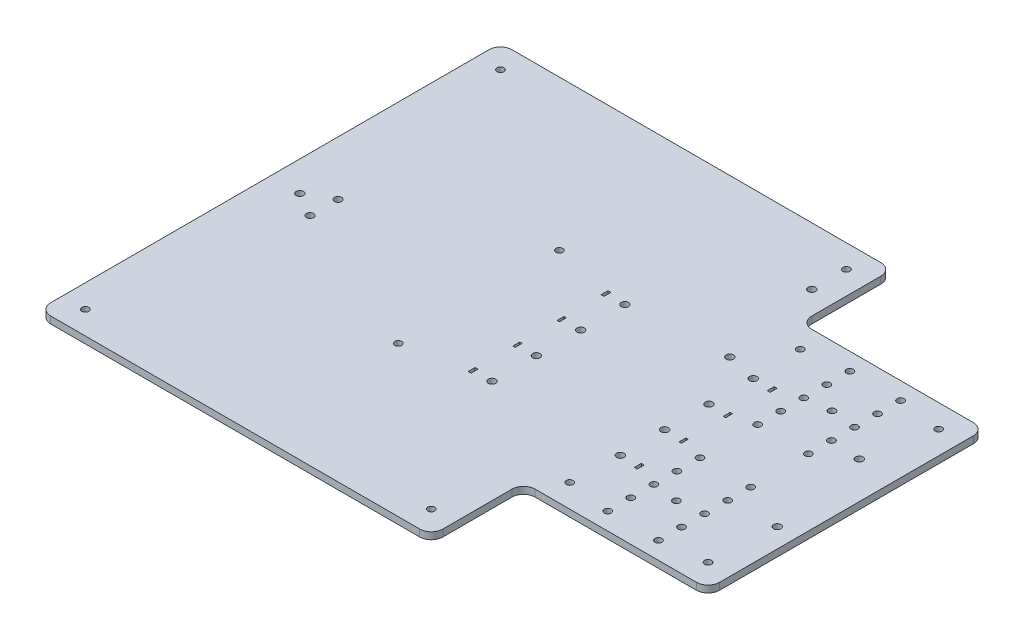
SolidWorks part; units mm, degrees
ref_plane "Front Plane" through (0, 0, 0) normal (0, 0, 1) x (1, 0, 0)
ref_plane "Top Plane" through (0, 0, 0) normal (0, 1, 0) x (1, 0, 0)
ref_plane "Right Plane" through (0, 0, 0) normal (1, 0, 0) x (0, 0, -1)
sketch "Sketch1" plane through (0, 0, 0) normal (0, 1, 0) x (1, 0, 0)
  line L0 (30.3119, 82.5397) -> (-139.6881, 82.5397)
  line L1 (-139.6881, 82.5397) -> (-139.6881, -117.4603)
  line L2 (-139.6881, -117.4603) -> (30.3119, -117.4603)
  line L3 (30.3119, -117.4603) -> (30.3119, -77.4603)
  line L4 (30.3119, -77.4603) -> (110.3119, -77.4603)
  line L5 (110.3119, -77.4603) -> (110.3119, 42.5397)
  line L6 (110.3119, 42.5397) -> (30.3119, 42.5397)
  line L7 (30.3119, 42.5397) -> (30.3119, 82.5397)
  line L8 (-139.6881, -17.4603) -> (110.3119, -17.4603) construction
  line L9 (-126.6881, -17.4603) -> (-116.1881, -11.3981) construction
  line L10 (-116.1881, -11.3981) -> (-116.1881, -23.5225) construction
  line L11 (-126.6881, -17.4603) -> (-116.1881, -23.5225) construction
  line L12 (70.3119, 42.5397) -> (70.3119, -77.4603) construction
  circle A0 centre (-119.6881, -17.4603) radius 7 construction
  circle A1 centre (-126.6881, -17.4603) radius 1.575
  circle A2 centre (-116.1881, -11.3981) radius 1.575
  circle A3 centre (-116.1881, -23.5225) radius 1.575
  circle A4 centre (-129.6881, 72.5397) radius 1.5
  circle A5 centre (20.3119, 72.5397) radius 1.5
  circle A6 centre (81.3119, 35.0397) radius 1.5
  circle A7 centre (81.3119, 25.0397) radius 1.5
  circle A8 centre (81.3119, 15.0397) radius 1.5
  circle A9 centre (81.3119, 5.0397) radius 1.5
  circle A10 centre (81.3119, -4.9603) radius 1.5
  circle A11 centre (59.3119, -4.9603) radius 1.5
  circle A12 centre (59.3119, 5.0397) radius 1.5
  circle A13 centre (59.3119, 15.0397) radius 1.5
  circle A14 centre (59.3119, 25.0397) radius 1.5
  circle A15 centre (59.3119, 35.0397) radius 1.5
  circle A16 centre (81.3119, -69.9603) radius 1.5
  circle A17 centre (81.3119, -59.9603) radius 1.5
  circle A18 centre (81.3119, -49.9603) radius 1.5
  circle A19 centre (81.3119, -39.9603) radius 1.5
  circle A20 centre (81.3119, -29.9603) radius 1.5
  circle A21 centre (59.3119, -29.9603) radius 1.5
  circle A22 centre (59.3119, -39.9603) radius 1.5
  circle A23 centre (59.3119, -49.9603) radius 1.5
  circle A24 centre (59.3119, -59.9603) radius 1.5
  circle A25 centre (59.3119, -69.9603) radius 1.5
  circle A26 centre (100.3119, 32.5397) radius 1.5
  circle A27 centre (40.3119, 32.5397) radius 1.5
  circle A28 centre (100.3119, -67.4603) radius 1.5
  circle A29 centre (40.3119, -67.4603) radius 1.5
  circle A30 centre (20.3119, -107.4603) radius 1.5
  circle A31 centre (-129.6881, -107.4603) radius 1.5
  point P0 (-139.6881, -17.4603)
  dimension "D6" = 14
  dimension "D8" = 3.15
  dimension "D13" = 3
  dimension "D14" = 3
  dimension "D20" = 3
  dimension "D1" = 250
  dimension "D2" = 80
  dimension "D3" = 40
  dimension "D4" = 200
  dimension "D5" = 20
  dimension "D7" = 60
  dimension "D9" = 10
  dimension "D10" = 10
  dimension "D11" = 10
  dimension "D12" = 10
  dimension "D15" = 7.5
  dimension "D16" = 11
  dimension "D18" = 10
  dimension "D19" = 10
  dimension "D17" = 5
extrude "Boss-Extrude1" add sketch "Sketch1" along normal blind 3
fillet "Fillet1" radius 5 8 edges at (30.3119, 1.5, -42.5397) (30.3119, 1.5, -82.5397) (-139.6881, 1.5, -82.5397) (-139.6881, 1.5, 117.4603) (110.3119, 1.5, -42.5397) (110.3119, 1.5, 77.4603) (30.3119, 1.5, 117.4603) (30.3119, 1.5, 77.4603)
sketch "Sketch2" plane through (0, 3, 0) normal (0, 1, 0) x (1, 0, 0)
  line L0 (110.3119, -17.4603) -> (-139.6881, -17.4603) construction
  line L1 (110.3119, -72.4603) -> (110.3119, 37.5397) construction
  line L2 (-139.6881, 77.5397) -> (-139.6881, -112.4603) construction
  line L3 (94.3119, -39.0503) -> (94.3119, 4.1297) construction
  line L4 (94.3119, -39.0503) -> (101.9319, -39.0503) construction
  line L5 (49.3119, -77.4603) -> (49.3119, 42.5397) construction
  line L6 (35.3119, -77.4603) -> (105.3119, -77.4603) construction
  line L7 (105.3119, 42.5397) -> (35.3119, 42.5397) construction
  line L8 (41.1019, -77.4603) -> (41.1019, 42.5397) construction
  line L9 (13.2919, -77.4603) -> (13.2919, 23.958) construction
  line L10 (49.8119, -6.3553) -> (49.8119, -9.3553)
  line L11 (49.8119, -28.5653) -> (48.8119, -28.5653)
  line L12 (49.8119, -28.5653) -> (49.8119, -25.5653)
  line L13 (49.8119, -25.5653) -> (48.8119, -25.5653)
  line L14 (48.8119, -28.5653) -> (48.8119, -25.5653)
  line L15 (49.8119, -28.5653) -> (48.8119, -25.5653) construction
  line L16 (49.8119, -25.5653) -> (48.8119, -28.5653) construction
  line L17 (49.9397, -47.7753) -> (48.6841, -47.7753)
  line L18 (49.9397, -47.7753) -> (49.9397, -44.7753)
  line L19 (49.9397, -44.7753) -> (48.6841, -44.7753)
  line L20 (48.6841, -47.7753) -> (48.6841, -44.7753)
  line L21 (49.9397, -47.7753) -> (48.6841, -44.7753) construction
  line L22 (49.9397, -44.7753) -> (48.6841, -47.7753) construction
  line L23 (49.8119, -9.3553) -> (48.8119, -9.3553)
  line L24 (48.8119, -6.3553) -> (48.8119, -9.3553)
  line L25 (49.8119, -6.3553) -> (48.8119, -6.3553)
  line L26 (49.9397, 9.8547) -> (48.6841, 9.8547)
  line L27 (48.6841, 12.8547) -> (48.6841, 9.8547)
  line L28 (49.9397, 12.8547) -> (48.6841, 12.8547)
  line L29 (49.9397, 12.8547) -> (49.9397, 9.8547)
  line L30 (-23.3559, 12.8547) -> (-23.3559, 9.8547)
  line L31 (-23.3559, 12.8547) -> (-22.1003, 12.8547)
  line L32 (-22.1003, 12.8547) -> (-22.1003, 9.8547)
  line L33 (-23.3559, 9.8547) -> (-22.1003, 9.8547)
  line L34 (-23.2281, -6.3553) -> (-22.2281, -6.3553)
  line L35 (-22.2281, -6.3553) -> (-22.2281, -9.3553)
  line L36 (-23.2281, -9.3553) -> (-22.2281, -9.3553)
  line L37 (-23.2281, -6.3553) -> (-23.2281, -9.3553)
  line L38 (-23.2281, -25.5653) -> (-22.2281, -25.5653)
  line L39 (-23.2281, -28.5653) -> (-22.2281, -28.5653)
  line L40 (-23.2281, -28.5653) -> (-23.2281, -25.5653)
  line L41 (-22.2281, -28.5653) -> (-22.2281, -25.5653)
  line L42 (-23.3559, -44.7753) -> (-22.1003, -44.7753)
  line L43 (-23.3559, -47.7753) -> (-22.1003, -47.7753)
  line L44 (-22.1003, -47.7753) -> (-22.1003, -44.7753)
  line L45 (-23.3559, -47.7753) -> (-23.3559, -44.7753)
  line L46 (-49.0625, -52.3853) -> (-49.0625, 17.4647) construction
  line L47 (20.3119, 14.3597) -> (20.3119, 57.5397) construction
  line L50 (70.3119, -51.2103) -> (70.3119, 16.2897) construction
  line L51 (20.3119, 14.3597) -> (27.9319, 14.3597) construction
  circle A0 centre (101.9319, -39.0503) radius 1.6
  circle A1 centre (94.3119, 4.1297) radius 1.6
  circle A2 centre (59.3119, -69.9603) radius 1.5 construction
  circle A3 centre (41.1019, -7.8553) radius 1.6
  circle A4 centre (41.1019, 11.3547) radius 1.6
  circle A5 centre (41.1019, -46.2753) radius 1.6
  circle A6 centre (41.1019, -27.0653) radius 1.6
  circle A7 centre (-14.5181, -7.8553) radius 1.6
  circle A8 centre (-14.5181, 11.3547) radius 1.6
  circle A9 centre (-14.5181, -27.0653) radius 1.6
  circle A10 centre (-14.5181, -46.2753) radius 1.6
  circle A11 centre (-49.0625, -52.3853) radius 1.5
  circle A12 centre (-49.0625, 17.4647) radius 1.5
  circle A17 centre (70.3119, -51.2103) radius 1.5
  circle A18 centre (70.3119, 16.2897) radius 1.5
  circle A19 centre (27.9319, 14.3597) radius 1.6
  circle A20 centre (20.3119, 57.5397) radius 1.6
  circle A21 centre (20.3119, 72.5397) radius 1.5 construction
  point P8 (94.3119, -17.4603)
  point P32 (49.3119, -27.0653)
  point P37 (49.3119, -46.2753)
  point P75 (-49.0625, -17.4603)
  point P81 (20.3119, 35.9497)
  point P87 (70.3119, -17.4603)
  dimension "D4" = 3.2
  dimension "D5" = 10
  dimension "D8" = 3.2
  dimension "D15" = 3
  dimension "D16" = 10
  dimension "D20" = 3
  dimension "D1" = 43.18
  dimension "D2" = 7.62
  dimension "D3" = 16
  dimension "D6" = 8.21
  dimension "D7" = 9.605
  dimension "D9" = 19.21
  dimension "D10" = 27.81
  dimension "D11" = 1
  dimension "D12" = 3
  dimension "D13" = 3
  dimension "D14" = 69.85
  dimension "D17" = 15
  dimension "D18" = 43.18
  dimension "D19" = 67.5
  dimension "D21" = 40
  dimension "D22" = 7.62
extrude "Cut-Extrude1" cut sketch "Sketch2" against normal up to surface (3 mm away) up to face at (7.8119, 0, 17.4603)
